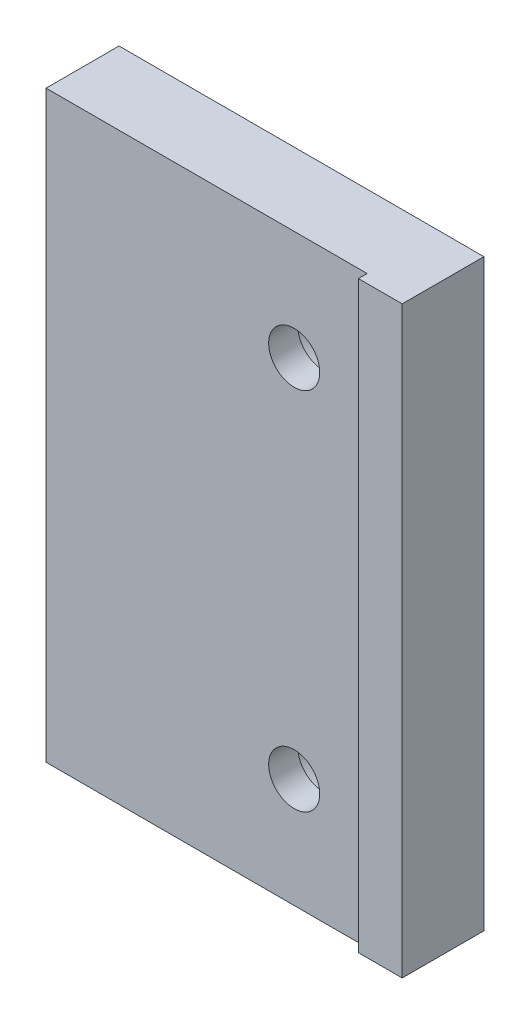
SolidWorks part; units mm, degrees
ref_plane "Front Plane" through (0, 0, 0) normal (0, 0, 1) x (1, 0, 0)
ref_plane "Top Plane" through (0, 0, 0) normal (0, 1, 0) x (1, 0, 0)
ref_plane "Right Plane" through (0, 0, 0) normal (1, 0, 0) x (0, 0, -1)
sketch "Sketch1" plane through (0, 0, 0) normal (0, 0, 1) x (1, 0, 0)
  line L0 (17, 32.5) -> (17, 7.5) construction
  line L1 (0, 0) -> (25, 0)
  line L2 (0, 0) -> (0, 40)
  line L3 (0, 40) -> (25, 40)
  line L4 (25, 0) -> (25, 40)
  line L5 (17, 7.5) -> (17, 0) construction
  line L6 (17, 32.5) -> (17, 40) construction
  circle A0 centre (17, 32.5) radius 1.75
  circle A1 centre (17, 7.5) radius 1.75
  dimension "D3" = 3.5
  dimension "D1" = 25
  dimension "D2" = 25
  dimension "D4" = 40
  dimension "D5" = 8
extrude "Boss-Extrude1" add sketch "Sketch1" along normal blind 5
sketch "Sketch2" plane through (0, 0, 5) normal (0, 0, 1) x (1, 0, 0)
  line L0 (0, 0) -> (25, 0) construction
  line L1 (25, 40) -> (22, 40)
  line L2 (25, 40) -> (25, 0)
  line L3 (25, 0) -> (22, 0)
  line L4 (22, 40) -> (22, 0)
  dimension "D1" = 3
extrude "Boss-Extrude2" add sketch "Sketch2" along normal blind 0.6
sketch "Sketch3" plane through (0, 0, 0) normal (0, 0, -1) x (-1, 0, 0)
  circle A0 centre (-17, 7.5) radius 3
  circle A1 centre (-17, 32.5) radius 3
  dimension "D1" = 6
extrude "Cut-Extrude1" cut sketch "Sketch3" against normal blind 3
